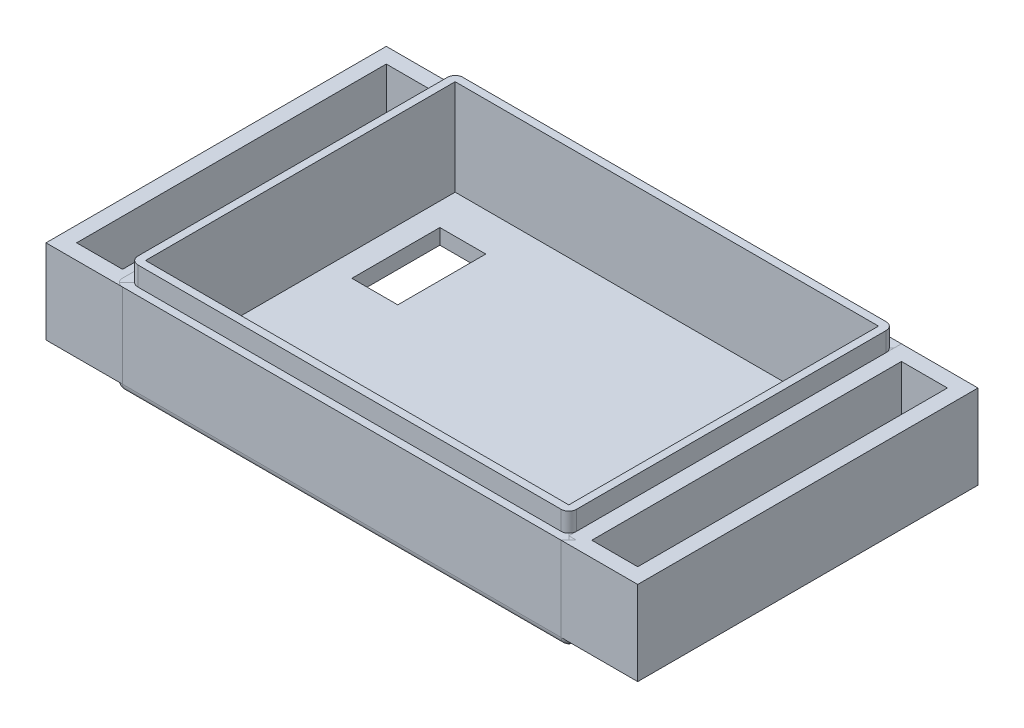
SolidWorks part; units mm, degrees
ref_plane "Front Plane" through (0, 0, 0) normal (0, 0, 1) x (1, 0, 0)
ref_plane "Top Plane" through (0, 0, 0) normal (0, 1, 0) x (1, 0, 0)
ref_plane "Right Plane" through (0, 0, 0) normal (1, 0, 0) x (0, 0, -1)
sketch "Sketch1" plane through (0, 0, 0) normal (0, 1, 0) x (1, 0, 0)
  line L1 (-29.655, 22.23) -> (29.655, 22.23)
  line L2 (-29.655, 22.23) -> (-29.655, -22.23)
  line L3 (-29.655, -22.23) -> (29.655, -22.23)
  line L4 (29.655, 22.23) -> (29.655, -22.23)
  dimension "D1" = 44.46
  dimension "D2" = 22.23
  dimension "D3" = 59.31
  dimension "D4" = 29.655
extrude "Boss-Extrude1" add sketch "Sketch1" along normal blind 2
sketch "Sketch2" plane through (0, 2, 0) normal (0, 1, 0) x (1, 0, 0)
  line L0 (27.655, -20.23) -> (27.655, 20.23)
  line L1 (27.655, 20.23) -> (-27.655, 20.23)
  line L2 (-27.655, 20.23) -> (-27.655, -20.23)
  line L3 (-27.655, -20.23) -> (27.655, -20.23)
  line L4 (-29.655, 22.23) -> (-29.655, -22.23)
  line L5 (-29.655, -22.23) -> (29.655, -22.23)
  line L6 (29.655, -22.23) -> (29.655, 22.23)
  line L7 (29.655, 22.23) -> (-29.655, 22.23)
  line L8 (-29.655, 22.23) -> (-29.655, -22.23)
  line L9 (-29.655, -22.23) -> (29.655, -22.23)
  line L10 (29.655, -22.23) -> (29.655, 22.23)
  line L11 (29.655, 22.23) -> (-29.655, 22.23)
  dimension "D1" = 0
  dimension "D2" = 2
extrude "Boss-Extrude2" add sketch "Sketch2" along normal blind 12.5
sketch "Sketch3" plane through (29.655, 0, 0) normal (1, 0, 0) x (0, 0, -1)
  line L1 (-21.23, 12) -> (-22.23, 12)
  line L2 (-21.23, 12) -> (-21.23, 14.5)
  line L3 (-21.23, 14.5) -> (-22.23, 14.5)
  line L4 (-22.23, 12) -> (-22.23, 14.5)
  dimension "D1" = 1
  dimension "D2" = 2.5
sketch "Sketch4" plane through (0, 14.5, 0) normal (0, 1, 0) x (1, 0, 0)
  line L0 (-29.655, -22.23) -> (29.655, -22.23) construction
  line L1 (-29.655, 22.23) -> (-29.655, -22.23) construction
  line L2 (29.655, 22.23) -> (-29.655, 22.23) construction
  line L3 (29.655, -22.23) -> (29.655, 22.23) construction
  line L4 (-29.655, -22.23) -> (29.655, -22.23)
  line L5 (-29.655, 22.23) -> (-29.655, -22.23)
  line L6 (29.655, 22.23) -> (-29.655, 22.23)
  line L7 (29.655, -22.23) -> (29.655, 22.23)
sweep "Cut-Sweep1" cut profiles "Sketch3" path "Sketch4"
fillet "Fillet1" radius 1 12 edges at (-29.655, 6, 22.23) (-29.655, 6, -22.23) (29.655, 6, -22.23) (-28.655, 13.25, -21.23) (28.655, 13.25, -21.23) (-28.655, 13.25, 21.23) (29.655, 0, 0) (0, 0, -22.23) (-29.655, 0, 0) (0, 0, 22.23)
sketch "Sketch5" plane through (0, 0, 0) normal (0, -1, 0) x (-1, 0, 0)
  line L0 (29.655, -21.23) -> (29.655, 21.23) construction
  line L1 (24.655, 3.73) -> (18.655, 3.73)
  line L2 (24.655, 3.73) -> (24.655, 15.23)
  line L3 (24.655, 15.23) -> (18.655, 15.23)
  line L4 (18.655, 3.73) -> (18.655, 15.23)
  line L5 (-27.655, 20.23) -> (27.655, 20.23) construction
  dimension "D1" = 11.5
  dimension "D2" = 6
  dimension "D3" = 5
  dimension "D4" = 5
extrude "Cut-Extrude1" cut sketch "Sketch5" against normal blind 10
sketch "Sketch6" plane through (0, 0, 0) normal (0, -1, 0) x (1, 0, 0)
  text T0 "A" font "Century Schoolbook" height in points 72
  dimension "D1" = 8
  dimension "D2" = 8
extrude "Boss-Extrude3" add sketch "Sketch6" along normal blind 2
sketch "Sketch7" plane through (0, 0, 0) normal (0, -1, 0) x (1, 0, 0)
  line L0 (-28.655, 20.23) -> (-28.655, -20.23) construction
  line L1 (28.655, -20.23) -> (28.655, 20.23) construction
  line L2 (-28.655, 20.23) -> (-28.655, -20.23)
  line L3 (28.655, -20.23) -> (28.655, 20.23)
  line L4 (-28.655, -20.23) -> (-28.655, -22.23)
  line L5 (-28.655, -22.23) -> (-38.655, -22.23)
  line L6 (-38.655, -22.23) -> (-38.655, 22.23)
  line L7 (-38.655, 22.23) -> (-28.655, 22.23)
  line L8 (-28.655, 22.23) -> (-28.655, 20.23)
  line L9 (28.655, -20.23) -> (28.655, -22.23)
  line L10 (28.655, -22.23) -> (38.6584, -22.23)
  line L11 (38.6584, -22.23) -> (38.6584, 22.23)
  line L12 (38.6584, 22.23) -> (28.655, 22.23)
  line L13 (28.655, 22.23) -> (28.655, 20.23)
  line L14 (-30.655, 20.23) -> (-30.655, -20.23)
  line L15 (-30.655, -20.23) -> (-30.655, -20.23)
  line L16 (-30.655, -20.23) -> (-36.655, -20.23)
  line L17 (-36.655, -20.23) -> (-36.655, 20.23)
  line L18 (-36.655, 20.23) -> (-30.655, 20.23)
  line L19 (-30.655, 20.23) -> (-30.655, 20.23)
  line L20 (36.6584, -20.23) -> (36.6584, 20.23)
  line L21 (36.6584, 20.23) -> (30.655, 20.23)
  line L22 (30.655, 20.23) -> (30.655, 20.23)
  line L23 (30.655, -20.23) -> (30.655, 20.23)
  line L24 (30.655, -20.23) -> (30.655, -20.23)
  line L25 (30.655, -20.23) -> (36.6584, -20.23)
  dimension "D1" = 10
  dimension "D2" = 10.0034
  dimension "D3" = 2
extrude "Boss-Extrude10" add sketch "Sketch7" against normal blind 11 from offset 1 separate body
